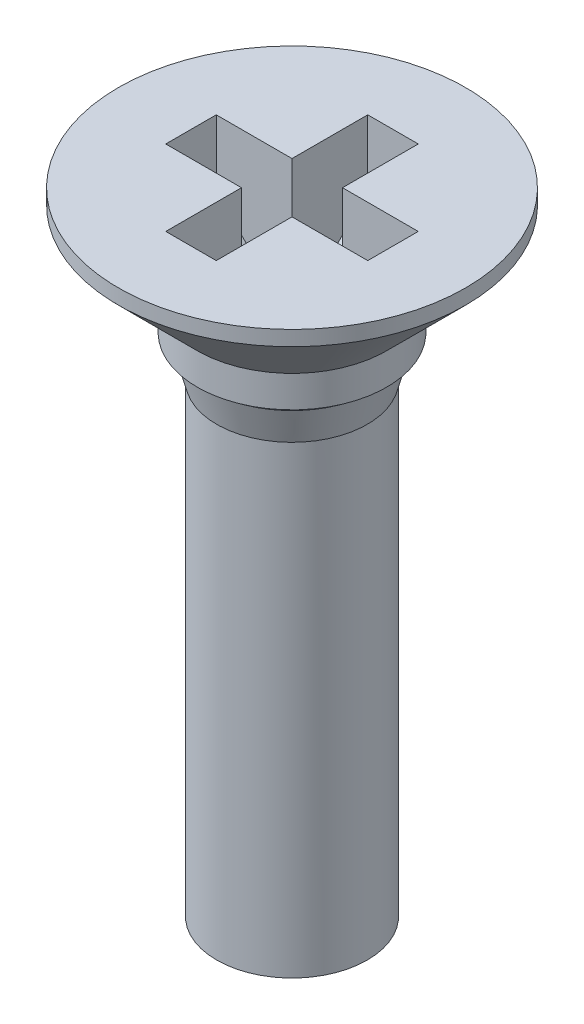
SolidWorks part; units mm, degrees
ref_plane "Vorderseite" through (0, 0, 0) normal (0, 0, 1) x (1, 0, 0)
ref_plane "Oben" through (0, 0, 0) normal (0, 1, 0) x (1, 0, 0)
ref_plane "Rechts" through (0, 0, 0) normal (1, 0, 0) x (0, 0, -1)
sketch "Skizze1" plane through (0, 0, 0) normal (0, 0, 1) x (1, 0, 0)
  line L0 (0, 0) -> (2.75, 0)
  line L1 (2.75, 0) -> (2.75, -0.2375)
  line L2 (2.75, -0.2375) -> (1.5, -1.4875)
  line L3 (1.3375, -1.9875) -> (1.3375, -2.1126)
  line L4 (1.3375, -2.1126) -> (1.1935, -2.65)
  line L5 (1.1935, -2.65) -> (1.1935, -8)
  line L6 (1.1935, -8) -> (0, -8)
  line L7 (0, 0) -> (0, -8) construction
  line L8 (0, 0) -> (0, -8)
  line L10 (1.5, -1.4875) -> (1.5, -1.9875)
  line L12 (1.5, -1.9875) -> (1.3375, -1.9875)
  point P3 (1.3375, -1.65)
  dimension "D1" = 45
  dimension "D2" = 15
  dimension "K" = 1.65
  dimension "DA" = 5.5
  dimension "DK" = 2.387
  dimension "L" = 8
  dimension "DG" = 3
  dimension "A" = 1
  dimension "DF" = 2.675
  dimension "P" = 0.5
revolve "Basis-Rotation" add sketch "Skizze1" angle 360 about L7
sketch "Skizze2" plane through (0, 0, 0) normal (0, 0, 1) x (1, 0, 0)
  line L0 (0, -2.1) -> (0, 0) construction
  line L1 (0, 0) -> (0, -8) construction
  line L2 (-0.55, -2.1) -> (0.55, -2.1)
  line L3 (1.6, 0) -> (1.6, -1.05)
  line L4 (1.6, -1.05) -> (0.55, -2.1)
  line L5 (1.6, 0) -> (-1.6, 0)
  line L6 (-1.6, -1.05) -> (-0.55, -2.1)
  line L7 (-1.6, 0) -> (-1.6, -1.05)
  line L8 (0, -1.05) -> (1.6, -1.05) construction
  line L9 (2.75, 0) -> (-2.75, 0) construction
  line L11 (1.5, -1.4875) -> (2.75, -0.2375) construction
  point P11 (0, 0)
  dimension "M" = 3.2
  dimension "T" = 2.1
extrude "Kreuzschlitz1 H" cut sketch "Skizze2" against normal blind 0.4 and the other way blind 0.4
sketch "Skizze3" plane through (0, 0, 0) normal (1, 0, 0) x (0, 0, -1)
  line L0 (0, -2.1) -> (0, 0) construction
  line L2 (-0.55, -2.1) -> (0.55, -2.1)
  line L3 (1.6, 0) -> (1.6, -1.05)
  line L4 (1.6, -1.05) -> (0.55, -2.1)
  line L5 (1.6, 0) -> (-1.6, 0)
  line L6 (-1.6, -1.05) -> (-0.55, -2.1)
  line L7 (-1.6, 0) -> (-1.6, -1.05)
  line L8 (0, -1.05) -> (1.6, -1.05) construction
  point P11 (0, 0)
extrude "Kreuzschlitz2 H" cut sketch "Skizze3" against normal blind 0.4 and the other way blind 0.4
sketch "Skizze4" plane through (2.4522, 0, -1.8507) normal (0, 1, 0) x (-1, 0, 0)
  line L0 (7.3522, 1.8507) -> (-2.4478, 1.8507) construction
  line L1 (2.4522, -3.0493) -> (2.4522, 6.7507) construction
  line L2 (-2.4478, 1.0342) -> (-2.4478, 2.6672)
  line L3 (-2.4478, 1.0342) -> (0.0059, 1.0342)
  line L4 (0.0059, 1.0342) -> (0.8191, 0.6258)
  line L5 (1.2273, 0.2176) -> (-1.0126, -1.6141)
  line L6 (0.8191, 0.6258) -> (-1.0126, -1.6141)
  line L7 (1.6357, -0.5956) -> (1.2273, 0.2176)
  line L8 (1.6357, -3.0493) -> (1.6357, -0.5956)
  line L9 (1.6357, -3.0493) -> (3.2687, -3.0493)
  line L10 (3.2687, -3.0493) -> (3.2687, -0.5956)
  line L11 (3.2687, -0.5956) -> (3.6772, 0.2176)
  line L12 (2.4522, 1.8507) -> (-1.0126, -1.6141) construction
  line L13 (4.0854, 0.6258) -> (5.917, -1.6141)
  line L14 (3.6772, 0.2176) -> (5.917, -1.6141)
  line L15 (4.8986, 1.0342) -> (4.0854, 0.6258)
  line L16 (7.3522, 1.0342) -> (4.8986, 1.0342)
  line L17 (7.3522, 1.0342) -> (7.3522, 2.6672)
  line L18 (7.3522, 2.6672) -> (4.8986, 2.6672)
  line L19 (4.8986, 2.6672) -> (4.0854, 3.0757)
  line L20 (3.6772, 3.4839) -> (5.917, 5.3156)
  line L21 (4.0854, 3.0757) -> (5.917, 5.3156)
  line L22 (3.2687, 4.2971) -> (3.6772, 3.4839)
  line L23 (3.2687, 6.7507) -> (3.2687, 4.2971)
  line L24 (1.6357, 6.7507) -> (3.2687, 6.7507)
  line L25 (1.6357, 6.7507) -> (1.6357, 4.2971)
  line L26 (1.6357, 4.2971) -> (1.2273, 3.4839)
  line L27 (0.8191, 3.0757) -> (-1.0126, 5.3156)
  line L28 (1.2273, 3.4839) -> (-1.0126, 5.3156)
  line L29 (0.0059, 2.6672) -> (0.8191, 3.0757)
  line L30 (-2.4478, 2.6672) -> (0.0059, 2.6672)
  circle A0 centre (2.4522, 1.8507) radius 4.9 construction
  circle A1 centre (2.4522, 1.8507) radius 2.0415 construction
  circle A2 centre (2.4522, 1.8507) radius 2.579 construction
  dimension "X2" = 4.083
  dimension "X1" = 5.158
  dimension "M" = 9.8
  dimension "D3" = 5.725
  dimension "X3" = 1.633
sketch "Sketch1" plane through (0, -8, 0) normal (0, -1, 0) x (1, 0, 0)
  circle A0 centre (0, 0) radius 1.1935
extrude "Boss-Extrude1" add sketch "Sketch1" along normal blind 2
